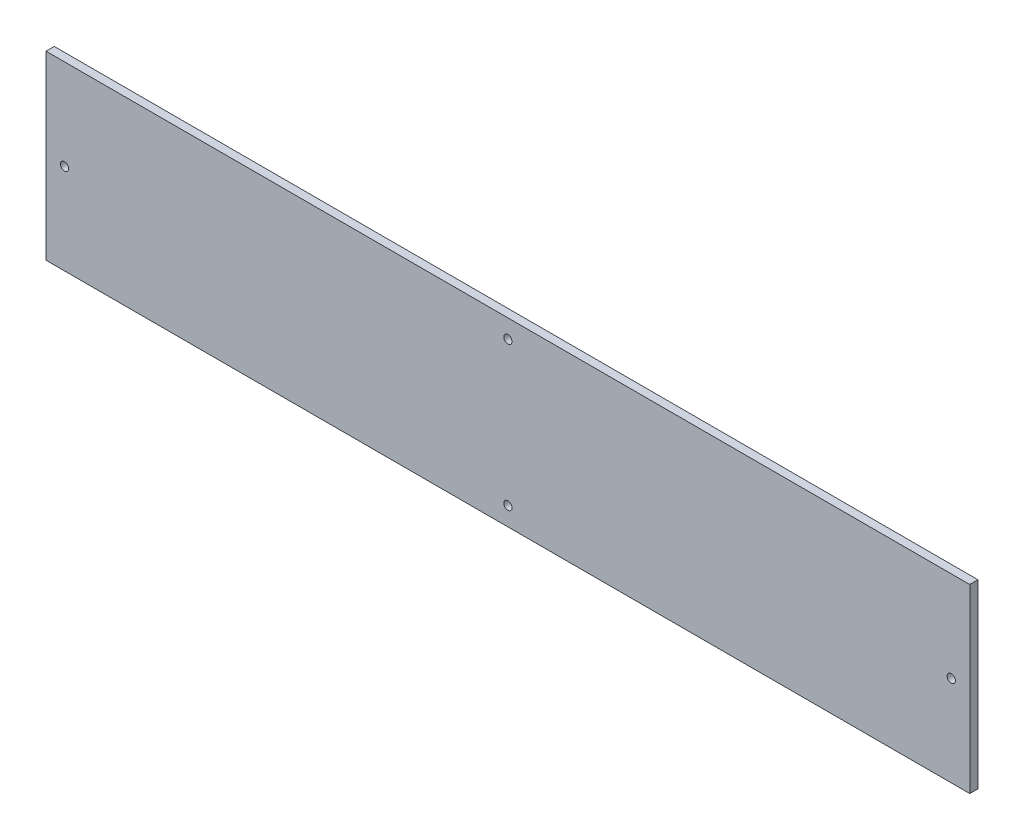
SolidWorks part; units mm, degrees
ref_plane "Piano frontale" through (0, 0, 0) normal (0, 0, 1) x (1, 0, 0)
ref_plane "Piano superiore" through (0, 0, 0) normal (0, 1, 0) x (1, 0, 0)
ref_plane "Piano destro" through (0, 0, 0) normal (1, 0, 0) x (0, 0, -1)
sketch "Schizzo1" plane through (0, 0, 0) normal (0, 0, 1) x (1, 0, 0)
  line L0 (-224.5, 351.6275) -> (-224.5, -66.2585) construction
  line L1 (0, 0) -> (-449, 0)
  line L2 (0, 0) -> (0, 88)
  line L3 (0, 88) -> (-449, 88)
  line L4 (-449, 0) -> (-449, 88)
  line L5 (-387.9788, 44) -> (120.8821, 44) construction
  circle A1 centre (-9, 44) radius 2
  circle A2 centre (-224.5, 79) radius 2
  circle A3 centre (-440, 44) radius 2
  circle A4 centre (-224.5, 9) radius 2
  point P9 (-224.5, 44)
  dimension "D3" = 4
  dimension "D2" = 4
  dimension "D1" = 449
  dimension "314" = 88
  dimension "D4" = 9
  dimension "D6" = 9
extrude "Estrusione-Estrusione1" add sketch "Schizzo1" along normal blind 4
